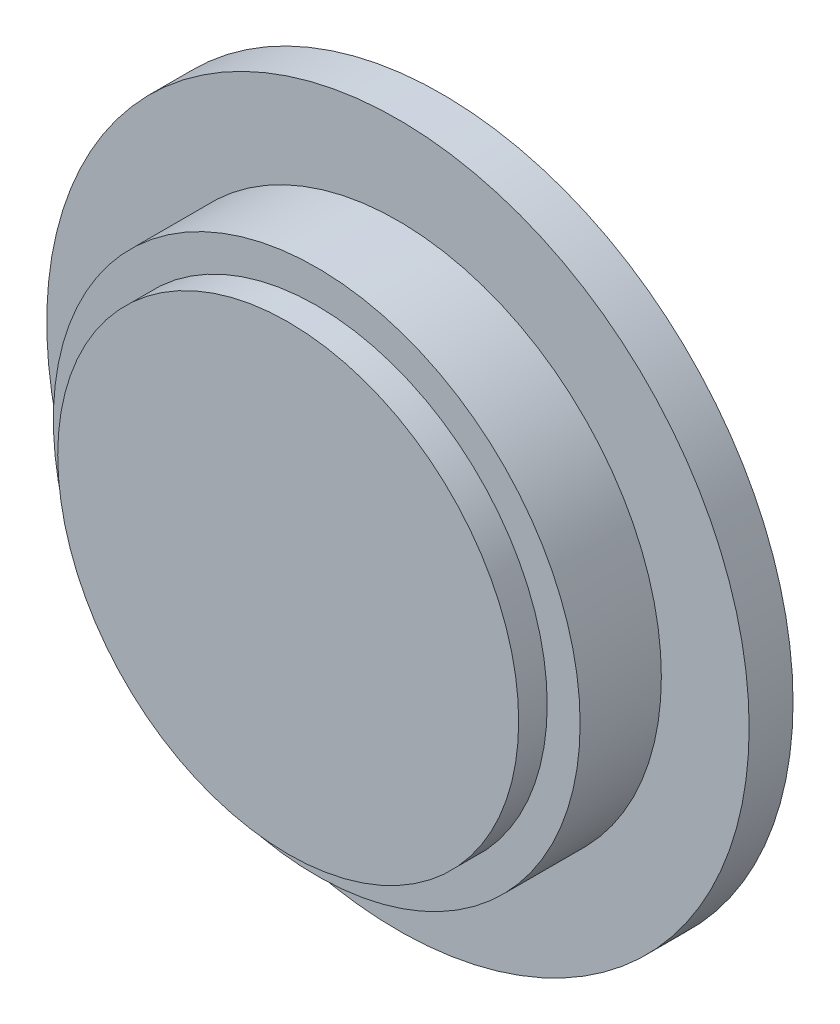
SolidWorks part; units mm, degrees
ref_plane "Front Plane" through (0, 0, 0) normal (0, 0, 1) x (1, 0, 0)
ref_plane "Top Plane" through (0, 0, 0) normal (0, 1, 0) x (1, 0, 0)
ref_plane "Right Plane" through (0, 0, 0) normal (1, 0, 0) x (0, 0, -1)
sketch "Sketch5" plane through (0, 0, 0) normal (0, 0, 1) x (1, 0, 0)
  circle A0 centre (0, 0) radius 160
extrude "Boss-Extrude3" add sketch "Sketch5" along normal blind 20
sketch "Sketch6" plane through (0, 0, 20) normal (0, 0, 1) x (1, 0, 0)
  circle A0 centre (0, 0) radius 120
extrude "Boss-Extrude4" add sketch "Sketch6" along normal blind 37
sketch "Sketch7" plane through (0, 0, 0) normal (0, 0, -1) x (-1, 0, 0)
  circle A0 centre (0, 0) radius 88
extrude "Boss-Extrude5" add sketch "Sketch7" along normal blind 10
sketch "Sketch12" plane through (0, 0, 57) normal (0, 0, 1) x (1, 0, 0)
  circle A0 centre (0, 0) radius 105
extrude "Boss-Extrude6" add sketch "Sketch12" along normal blind 13
